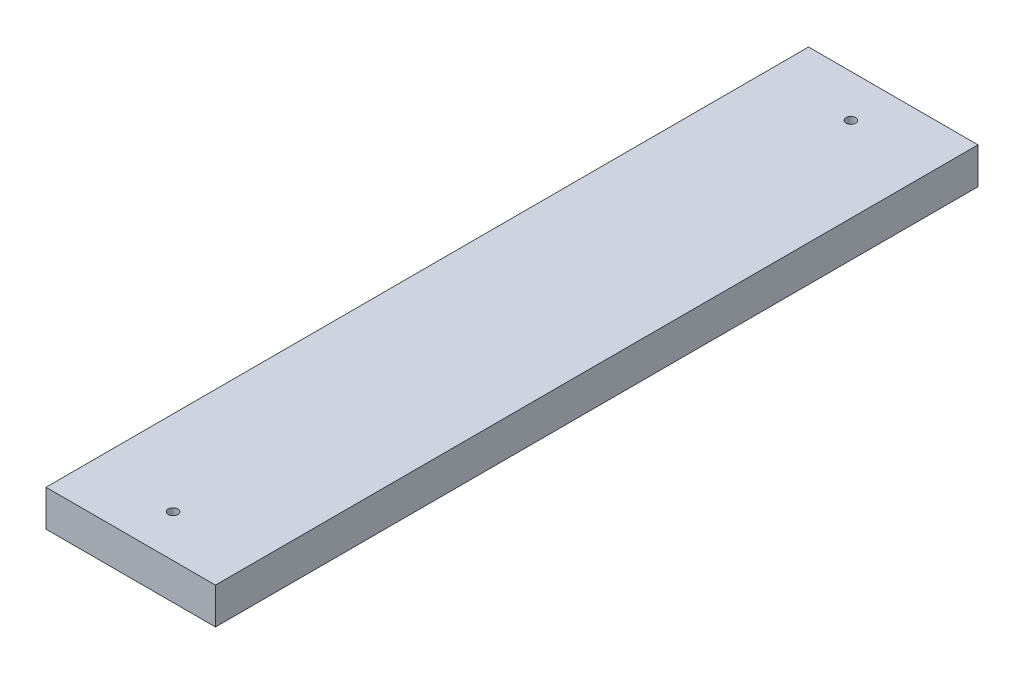
SolidWorks part; units mm, degrees
ref_plane "Front Plane" through (0, 0, 0) normal (0, 0, 1) x (1, 0, 0)
ref_plane "Top Plane" through (0, 0, 0) normal (0, 1, 0) x (1, 0, 0)
ref_plane "Right Plane" through (0, 0, 0) normal (1, 0, 0) x (0, 0, -1)
sketch "Sketch1" plane through (0, 0, 0) normal (0, 1, 0) x (1, 0, 0)
  line L0 (0, 140) -> (0, -140) construction
  line L1 (-35, 157.5) -> (35, 157.5)
  line L2 (-35, 157.5) -> (-35, -157.5)
  line L3 (-35, -157.5) -> (35, -157.5)
  line L4 (35, 157.5) -> (35, -157.5)
  line L5 (-35, 157.5) -> (35, -157.5) construction
  line L6 (-35, -157.5) -> (35, 157.5) construction
  circle A0 centre (0, 140) radius 2
  circle A1 centre (0, -140) radius 2
  point P0 (0, 0)
  dimension "D3" = 4
  dimension "D1" = 70
  dimension "D2" = 315
  dimension "D4" = 280
extrude "Boss-Extrude1" add sketch "Sketch1" along normal blind 15
